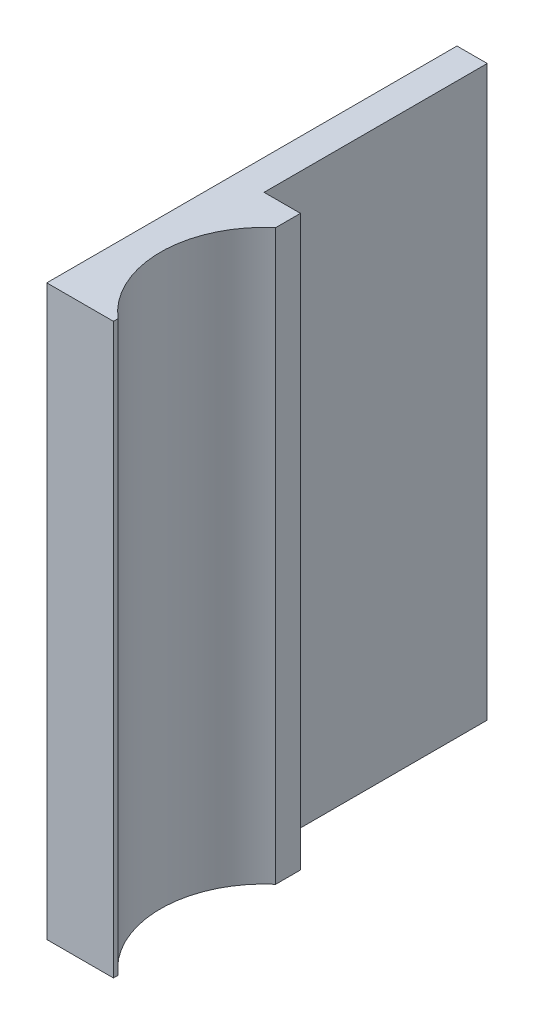
SolidWorks part; units mm, degrees
ref_plane "Front Plane" through (0, 0, 0) normal (0, 0, 1) x (1, 0, 0)
ref_plane "Top Plane" through (0, 0, 0) normal (0, 1, 0) x (1, 0, 0)
ref_plane "Right Plane" through (0, 0, 0) normal (1, 0, 0) x (0, 0, -1)
sketch "Sketch1" plane through (0, 0, 0) normal (0, 1, 0) x (1, 0, 0)
  line L0 (-0.3225, 21.5265) -> (-0.3225, -21.5265) construction
  line L1 (3.4975, -21.5265) -> (-3.4975, -21.5265)
  line L2 (3.4975, -21.5265) -> (3.4975, -21.0393)
  line L3 (-0.3225, 21.5265) -> (-3.4975, 21.5265)
  line L4 (-3.4975, -21.5265) -> (-3.4975, 21.5265)
  line L5 (3.4975, -21.5265) -> (-3.4975, 21.5265) construction
  line L6 (3.4975, 21.5265) -> (-3.4975, -21.5265) construction
  line L7 (-0.3225, -12.7665) -> (10.5455, -12.7665) construction
  line L8 (3.4975, -4.4937) -> (3.4975, -1.8985)
  line L12 (3.4975, -1.8985) -> (-0.3225, -1.8985)
  line L13 (-0.3225, 21.5265) -> (-0.3225, -1.8985)
  arc A0 (3.4975, -4.4937) -> (3.4975, -21.0393) centre (10.5455, -12.7665) ccw
  point P0 (0, 0)
  point P8 (3.4975, -21.0865)
  point P11 (3.4975, -1.8985)
  dimension "D1" = 6.995
  dimension "D2" = 43.053
  dimension "D3" = 3.175
  dimension "D4" = 0.44
  dimension "D5" = 8.32
  dimension "D6" = 10.868
  dimension "D7" = 10.868
extrude "Boss-Extrude1" add sketch "Sketch1" along normal blind 59.69
sketch "Sketch2" plane through (-0.3225, 0, 0) normal (1, 0, 0) x (0, 0, -1)
  line L0 (9.814, 59.69) -> (9.814, 0) construction
  line L1 (-1.8985, 59.69) -> (21.5265, 59.69) construction
  line L2 (-1.8985, 0) -> (21.5265, 0) construction
  line L4 (19.893, 9.352) -> (-0.265, 9.352)
  line L5 (19.893, 9.352) -> (19.893, 50.338)
  line L6 (19.893, 50.338) -> (-0.265, 50.338)
  line L7 (-0.265, 9.352) -> (-0.265, 50.338)
  line L8 (19.893, 9.352) -> (-0.265, 50.338) construction
  line L9 (19.893, 50.338) -> (-0.265, 9.352) construction
  point P6 (9.814, 29.845)
  dimension "D1" = 40.986
  dimension "D2" = 20.158
